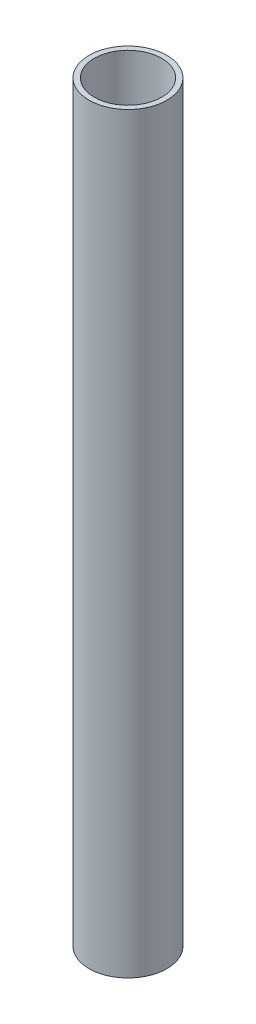
SolidWorks part; units mm, degrees
ref_plane "Front Plane" through (0, 0, 0) normal (0, 0, 1) x (1, 0, 0)
ref_plane "Top Plane" through (0, 0, 0) normal (0, 1, 0) x (1, 0, 0)
ref_plane "Right Plane" through (0, 0, 0) normal (1, 0, 0) x (0, 0, -1)
sketch "Sketch1" plane through (0, 0, 0) normal (0, 1, 0) x (1, 0, 0)
  circle A0 centre (0, 0) radius 6.5
  circle A1 centre (0, 0) radius 7.5
  dimension "D1" = 15
  dimension "D2" = 13
extrude "Boss-Extrude1" add sketch "Sketch1" along normal blind 145
